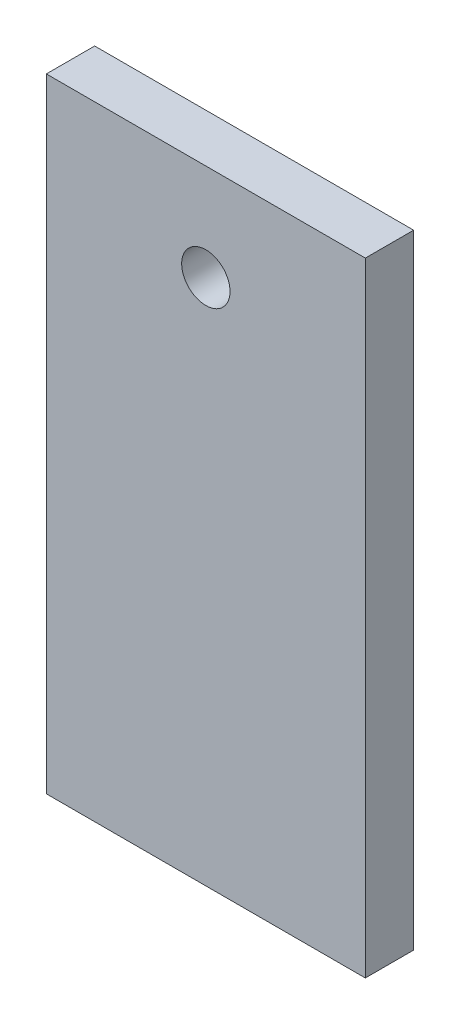
SolidWorks part; units mm, degrees
ref_plane "前视" through (0, 0, 0) normal (0, 0, 1) x (1, 0, 0)
ref_plane "上视" through (0, 0, 0) normal (0, 1, 0) x (1, 0, 0)
ref_plane "右视" through (0, 0, 0) normal (1, 0, 0) x (0, 0, -1)
sketch "草图1" plane through (0, 0, 0) normal (0, 0, 1) x (1, 0, 0)
  line L1 (0, 0) -> (66, 0)
  line L2 (0, 0) -> (0, 129)
  line L3 (0, 129) -> (66, 129)
  line L4 (66, 0) -> (66, 129)
  circle A0 centre (33, 109) radius 5
  dimension "D3" = 10
  dimension "D1" = 129
  dimension "D2" = 66
  dimension "D4" = 20
extrude "凸台-拉伸1" add sketch "草图1" along normal blind 10
